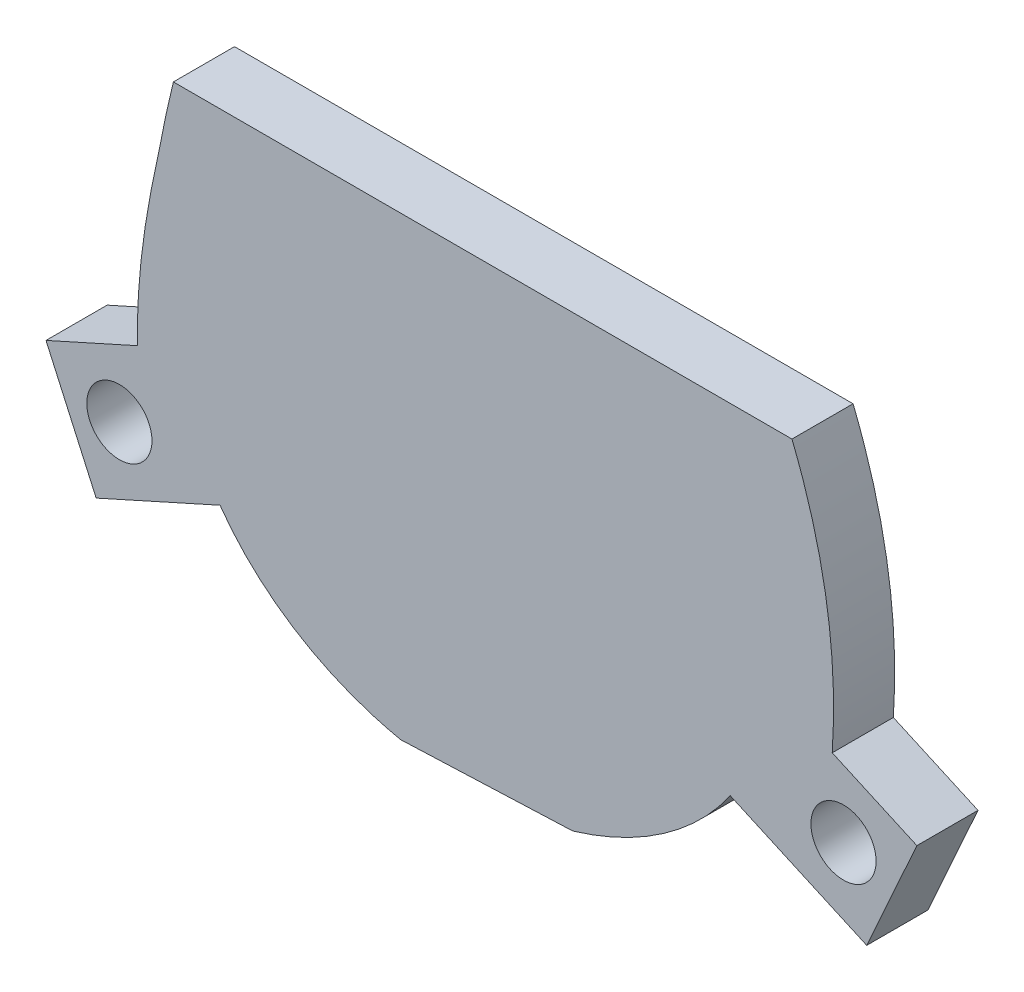
SolidWorks part; units mm, degrees
ref_plane "Front Plane" through (0, 0, 0) normal (0, 0, 1) x (1, 0, 0)
ref_plane "Top Plane" through (0, 0, 0) normal (0, 1, 0) x (1, 0, 0)
ref_plane "Right Plane" through (0, 0, 0) normal (1, 0, 0) x (0, 0, -1)
sketch "Sketch1" plane through (0, 0, 0) normal (0, 0, 1) x (1, 0, 0)
  line L0 (7.5717, 3.9039) -> (6.4161, 3.9039)
  line L1 (-6.281, 3.9039) -> (-7.6093, 3.9039)
  line L2 (2.1911, -7.1172) -> (-2.0293, -7.288)
  line L3 (-9.5051, -5.8894) -> (-6.4647, -4.5216)
  line L6 (9.4068, -5.9406) -> (10.6376, -3.2047) construction
  line L7 (8.5604, -2.2702) -> (10.6376, -3.2047) construction
  line L13 (6.4161, 3.9039) -> (-6.281, 3.9039)
  line L14 (9.4068, -5.9406) -> (10.6376, -3.2047)
  line L15 (8.5604, -2.2702) -> (10.6376, -3.2047)
  line L17 (9.4068, -5.9406) -> (6.0561, -4.4332)
  line L18 (-9.5051, -5.8894) -> (-10.7359, -3.1536) construction
  line L19 (-8.4916, -2.1439) -> (-10.7359, -3.1536) construction
  line L21 (-9.5051, -5.8894) -> (-10.7359, -3.1536)
  line L22 (-8.4916, -2.1439) -> (-10.7359, -3.1536)
  circle A5 centre (8.8367, -4.0393) radius 0.8
  circle A6 centre (-8.9349, -3.9881) radius 0.8
  ellipse E0 centre (-0.2114, -1.4909) end of major axis (-7.4369, -1.6156) minor radius 5.9792 (-7.4369, -1.6156) -> (-3.527, -6.8219) ccw construction
  ellipse E1 centre (-0.2114, -1.4909) end of major axis (-7.4369, -1.6156) minor radius 5.9792 (-6.4647, -4.5216) -> (-2.0293, -7.288) ccw
  ellipse E2 centre (-0.2114, -1.4909) end of major axis (-7.4369, -1.6156) minor radius 5.9792 (2.1911, -7.1172) -> (6.0561, -4.4332) ccw
  parabola Q1 (8.5604, -2.2702) -> (6.9904, 5.1717) focus (1.7083, -0.2748) apex (8.442, 0.7336) construction
  parabola Q3 (8.5604, -2.2702) -> (7.5717, 3.9039) focus (1.7083, -0.2748) apex (8.442, 0.7336)
  spline S2 degree 3 poles (1145.5894, 9879.6871) (745.6861, -230.709) (-521.8286, 8.456) (340.882, 89.065) (-10004.8601, -86.445) knots -13.90745 -13.90745 -13.90745 -13.90745 0.658814 10.395223 10.395223 10.395223 10.395223 only from (-8.4916, -2.1439) to (-7.9553, 2.2951) construction
  spline S3 degree 3 poles (-8591.6732, 5129.2401) (8563.947, -5238.1398) (-8595.2027, 5216.5281) (8621.9256, -5045.3874) knots -6.504454 -6.504454 -6.504454 -6.504454 7.713074 7.713074 7.713074 7.713074 only from (-7.9553, 2.2951) to (-7.3183, 4.8458) construction
  spline S13 degree 3 poles (-8.4916, -2.1439) (-8.4975, -1.7531) (-8.4612, -0.2602) (-8.1977, 1.2158) (-7.9553, 2.2951) knots 0.593149 0.593149 0.593149 0.593149 0.658814 0.844124 0.844124 0.844124 0.844124
  spline S14 degree 3 poles (-7.9553, 2.2951) (-7.8506, 2.8336) (-7.7457, 3.3762) (-7.6093, 3.9039) knots 0.598754 0.598754 0.598754 0.598754 0.708182 0.708182 0.708182 0.708182
extrude "Boss-Extrude1" add sketch "Sketch1" against normal blind 1.5 from offset 2
